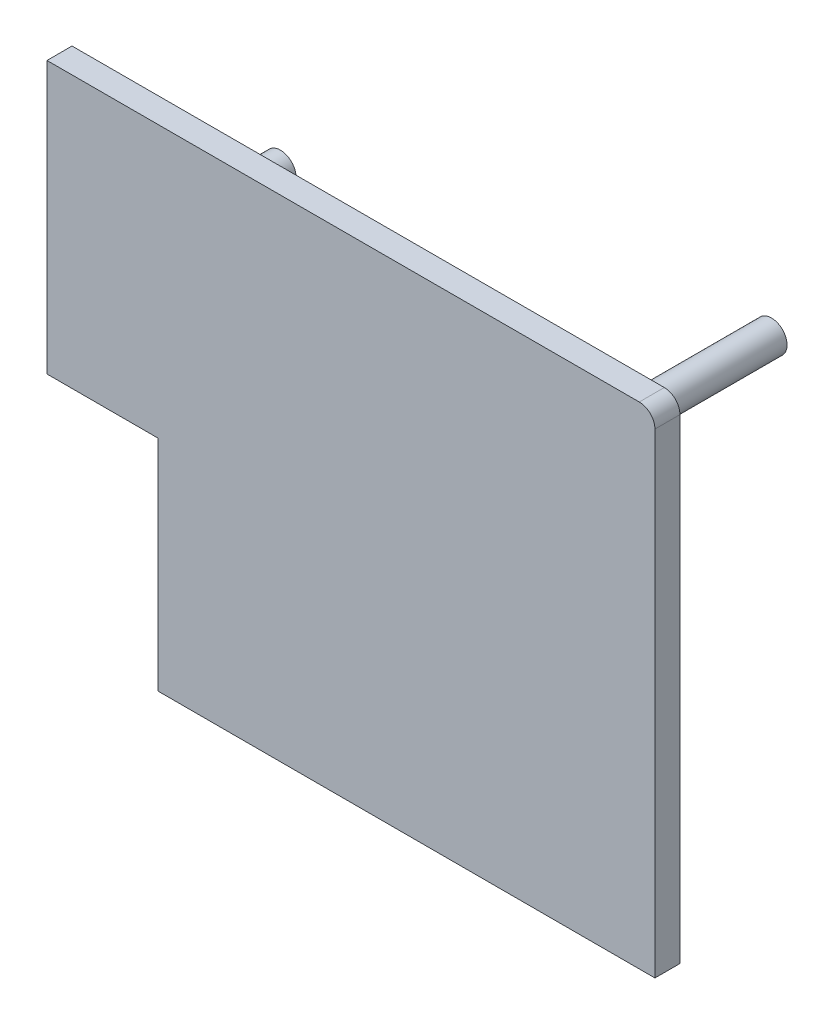
SolidWorks part; units mm, degrees
ref_plane "Front Plane" through (0, 0, 0) normal (0, 0, 1) x (1, 0, 0)
ref_plane "Top Plane" through (0, 0, 0) normal (0, 1, 0) x (1, 0, 0)
ref_plane "Right Plane" through (0, 0, 0) normal (1, 0, 0) x (0, 0, -1)
sketch "Sketch4" plane through (0, 0, 0) normal (0, 0, 1) x (1, 0, 0)
  line L0 (214.0833, -91.4262) -> (214.0833, -108.788)
  line L1 (101.9898, -91.4981) -> (251.9494, -91.4019) construction
  line L2 (214.0833, -108.788) -> (221.1667, -108.788)
  line L3 (221.1667, -108.788) -> (221.1667, -122.7939)
  line L4 (221.1667, -122.7939) -> (252.95, -122.7939)
  line L5 (252.95, -92.4019) -> (252.95, -139.1519) construction
  line L6 (214.0833, -91.4262) -> (251.9494, -91.4019)
  line L7 (252.95, -92.4019) -> (252.95, -122.7939)
  arc A0 (251.9494, -91.4019) -> (252.95, -92.4019) centre (251.95, -92.4019) cw
extrude "Boss-Extrude1" add sketch "Sketch4" along normal blind 1.6
sketch "Sketch5" plane through (0, 0, 0) normal (0, 0, -1) x (-1, 0, 0)
  circle A0 centre (-224.8535, -120.5321) radius 1
  circle A1 centre (-218.4085, -100.5273) radius 1
  circle A2 centre (-241.552, -120.5321) radius 1
  circle A3 centre (-249.7967, -94.1241) radius 1
extrude "Boss-Extrude2" add sketch "Sketch5" along normal blind 9
